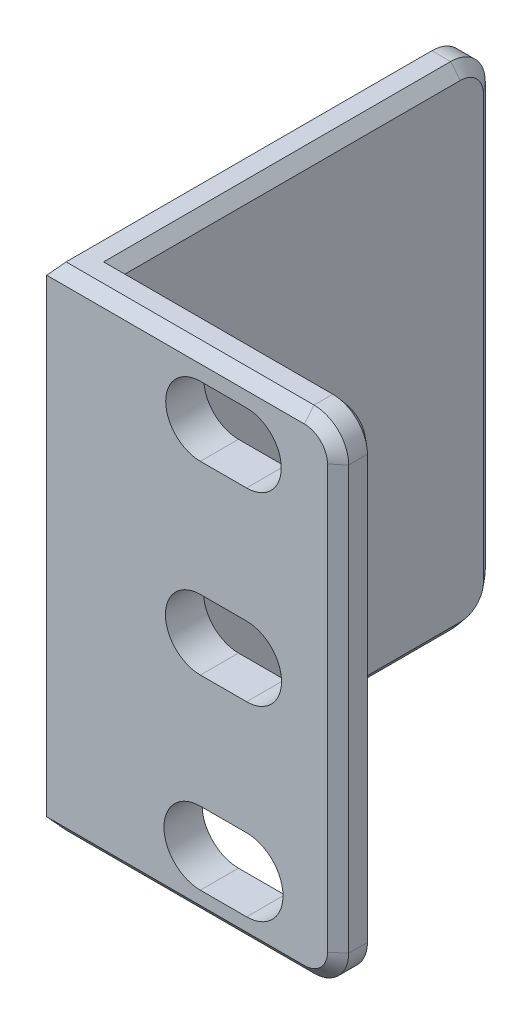
SolidWorks part; units mm, degrees
ref_plane "Спереди" through (0, 0, 0) normal (0, 0, 1) x (1, 0, 0)
ref_plane "Сверху" through (0, 0, 0) normal (0, 1, 0) x (1, 0, 0)
ref_plane "Справа" through (0, 0, 0) normal (1, 0, 0) x (0, 0, -1)
sketch "Эскиз1" plane through (0, 0, 0) normal (0, 1, 0) x (1, 0, 0)
  line L0 (0, 0) -> (25.3, 0)
  line L1 (25.3, 0) -> (25.3, 3.3)
  line L2 (25.3, 3.3) -> (3.3, 3.3)
  line L3 (3.3, 3.3) -> (3.3, 35.5)
  line L4 (3.3, 35.5) -> (0, 35.5)
  line L5 (0, 35.5) -> (0, 0)
  dimension "D1" = 3.3
  dimension "D2" = 35.5
  dimension "D3" = 25.3
extrude "Бобышка-Вытянуть1" add sketch "Эскиз1" along normal mid plane 42.6
sketch "Эскиз2" plane through (0, 0, 0) normal (0, 0, 1) x (1, 0, 0)
  line L0 (17.3, 16) -> (13.3, 16) construction
  line L1 (17.3, 13) -> (13.3, 13)
  line L2 (17.3, 19) -> (13.3, 19)
  line L3 (17.3, 0) -> (13.3, 0) construction
  line L4 (17.3, -3.0226) -> (13.3, -3.0226)
  line L5 (17.3, 3.0226) -> (13.3, 3.0226)
  line L6 (17.3, -16) -> (13.3, -16) construction
  line L7 (17.3, -19.1508) -> (13.3, -19.1508)
  line L8 (17.3, -12.8492) -> (13.3, -12.8492)
  line L9 (25.3, 21.3) -> (25.3, -21.3) construction
  arc A0 (17.3, 13) -> (17.3, 19) centre (17.3, 16) ccw
  arc A1 (13.3, 19) -> (13.3, 13) centre (13.3, 16) ccw
  arc A2 (17.3, -3.0226) -> (17.3, 3.0226) centre (17.3, 0) ccw
  arc A3 (13.3, 3.0226) -> (13.3, -3.0226) centre (13.3, 0) ccw
  arc A4 (17.3, -19.1508) -> (17.3, -12.8492) centre (17.3, -16) ccw
  arc A5 (13.3, -12.8492) -> (13.3, -19.1508) centre (13.3, -16) ccw
  point P2 (15.3, 16)
  point P7 (15.3, 0)
  point P15 (15.3, -16)
  point P22 (10.3, 16)
  point P24 (20.3, 16)
  dimension "D1" = 16
  dimension "D2" = 16
  dimension "D3" = 4
  dimension "D4" = 10
  dimension "D5" = 6
  dimension "D6" = 10
extrude "Вырез-Вытянуть1" cut sketch "Эскиз2" against normal blind 42.6
fillet "Скругление1" radius 3 4 edges at (25.3, -21.3, -1.65) (25.3, 21.3, -1.65) (1.65, -21.3, -35.5) (1.65, 21.3, -35.5)
chamfer "Фаска1" distance 1 angle 40 20 edges at (0, -21.3, -16.25) (11.15, -21.3, 0) (0, -20.4213, -34.6213) (24.4213, -20.4213, 0) (0, 0, -35.5) (25.3, 0, 0) (0, 20.4213, -34.6213) (24.4213, 20.4213, 0) (0, 21.3, -16.25) (11.15, 21.3, 0) (3.3, -21.3, -17.9) (12.8, -21.3, -3.3) (3.3, -20.4213, -34.6213) (24.4213, -20.4213, -3.3) (3.3, 0, -35.5) (25.3, 0, -3.3) (3.3, 20.4213, -34.6213) (24.4213, 20.4213, -3.3) (3.3, 21.3, -17.9) (12.8, 21.3, -3.3)
